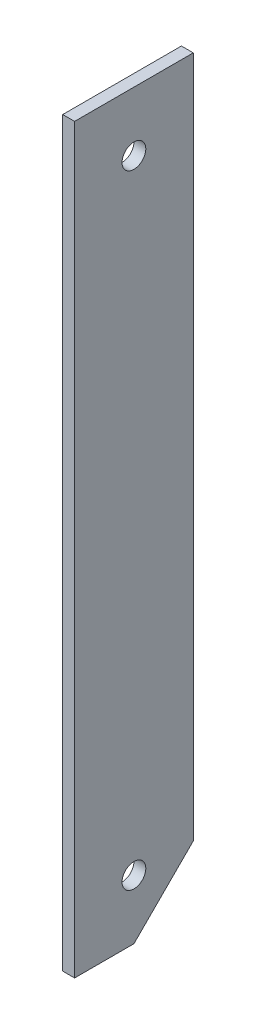
SolidWorks part; units mm, degrees
ref_plane "Front Plane" through (0, 0, 0) normal (0, 0, 1) x (1, 0, 0)
ref_plane "Top Plane" through (0, 0, 0) normal (0, 1, 0) x (1, 0, 0)
ref_plane "Right Plane" through (0, 0, 0) normal (1, 0, 0) x (0, 0, -1)
sketch "Sketch1" plane through (0, 0, 0) normal (1, 0, 0) x (0, 0, -1)
  line L0 (0, 125) -> (0, -125) construction
  line L1 (-20, 125) -> (20, 125)
  line L2 (-20, 125) -> (-20, -125)
  line L3 (-20, -125) -> (20, -125)
  line L4 (20, 125) -> (20, -125)
  line L5 (-20, 125) -> (20, -125) construction
  line L6 (-20, -125) -> (20, 125) construction
  line L7 (0, 0) -> (45.6121, 0) construction
  circle A0 centre (0, 105) radius 4
  circle A1 centre (0, -105) radius 4
  point P0 (0, 0)
  dimension "D3" = 20
  dimension "D1" = 125
  dimension "D2" = 40
  dimension "D4" = 125
  dimension "D6" = 20
  dimension "D7" = 20
  dimension "D8" = 20
extrude "Boss-Extrude1" add sketch "Sketch1" along normal blind 4
chamfer "Chamfer3" distance 20 angle 45 1 edges at (2, -125, -20)
